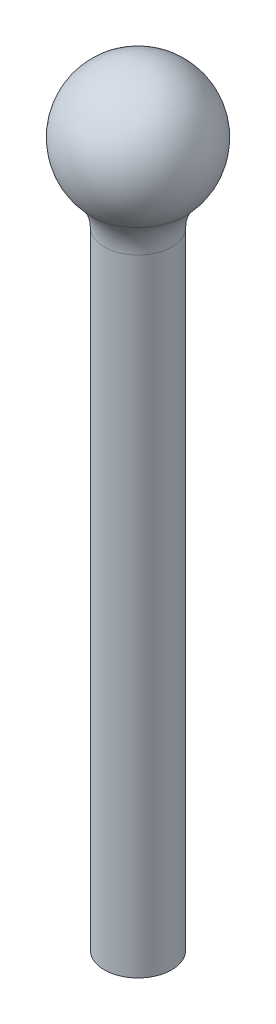
SolidWorks part; units mm, degrees
ref_plane "Front Plane" through (0, 0, 0) normal (0, 0, 1) x (1, 0, 0)
ref_plane "Top Plane" through (0, 0, 0) normal (0, 1, 0) x (1, 0, 0)
ref_plane "Right Plane" through (0, 0, 0) normal (1, 0, 0) x (0, 0, -1)
sketch "Sketch1" plane through (0, 0, 0) normal (0, 0, 1) x (1, 0, 0)
  line L0 (0, 6.75) -> (0, -18.25)
  line L1 (1.25, -73.25) -> (3.5, -73.25)
  line L2 (3.5, -73.25) -> (3.5, -8.1125)
  line L3 (1.25, -73.25) -> (1.25, -18.25)
  line L4 (1.25, -18.25) -> (0, -18.25)
  arc A0 (4.883, -4.6604) -> (0, 6.75) centre (0, 0) ccw
  arc A1 (3.5, -8.1125) -> (4.883, -4.6604) centre (8.5, -8.1125) cw
  dimension "D1" = 13.5
  dimension "D4" = 5
  dimension "D2" = 3.5
  dimension "D3" = 80
  dimension "D5" = 55
  dimension "D6" = 1.25
revolve "Revolve1" add sketch "Sketch1" angle 360 about L0
